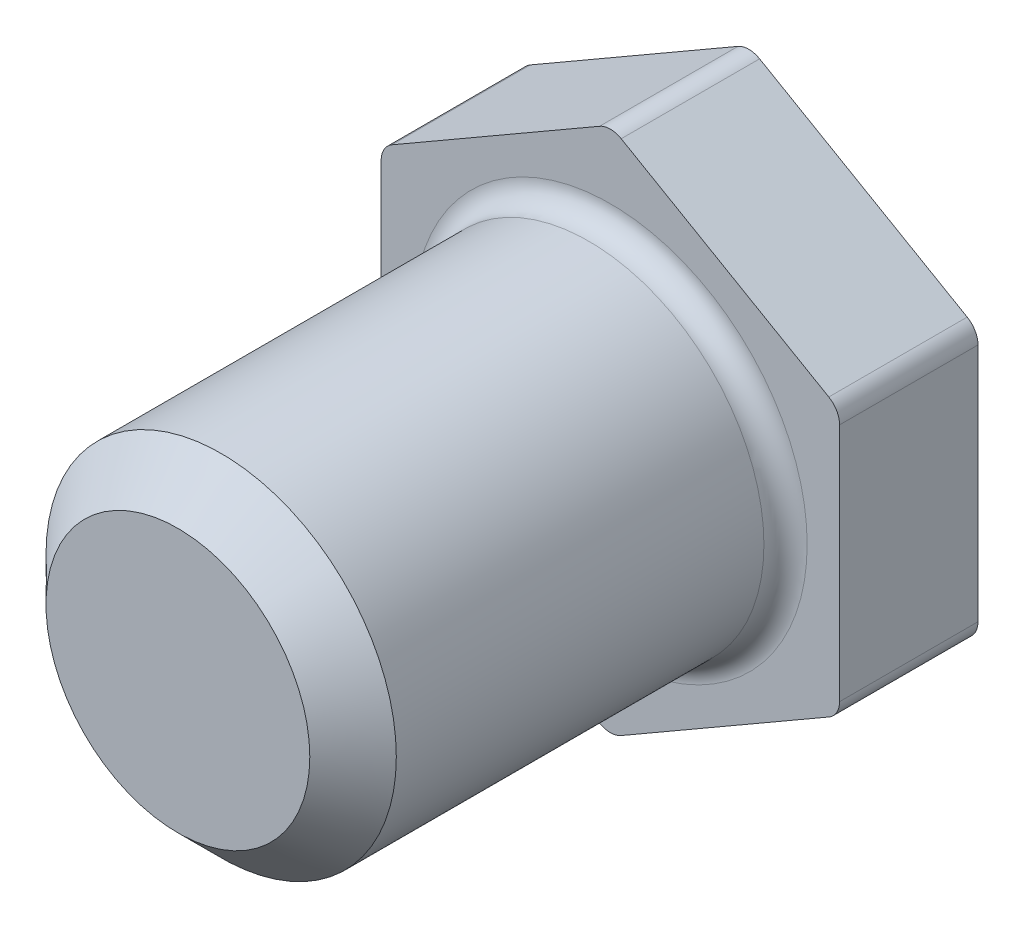
SolidWorks part; units mm, degrees
material "Anycubic PLA V3.0"
ref_plane "Front Plane" through (0, 0, 0) normal (0, 0, 1) x (1, 0, 0)
ref_plane "Top Plane" through (0, 0, 0) normal (0, 1, 0) x (1, 0, 0)
ref_plane "Right Plane" through (0, 0, 0) normal (1, 0, 0) x (0, 0, -1)
sketch "Sketch1" plane through (0, 0, 0) normal (0, 0, 1) x (1, 0, 0)
  line L0 (5.3, 3.06) -> (0, 6.1199)
  line L7 (0, 8.35) -> (-7.2313, 4.175)
  line L8 (-7.2313, 4.175) -> (-7.2313, -4.175)
  line L9 (-7.2313, -4.175) -> (0, -8.35)
  line L10 (0, -8.35) -> (7.2313, -4.175)
  line L11 (7.2313, -4.175) -> (7.2313, 4.175)
  line L12 (7.2313, 4.175) -> (0, 8.35)
  line L13 (0, 6.1199) -> (-5.3, 3.06)
  line L14 (-5.3, 3.06) -> (-5.3, -3.06)
  line L15 (-5.3, -3.06) -> (0, -6.1199)
  line L16 (0, -6.1199) -> (5.3, -3.06)
  line L17 (5.3, -3.06) -> (5.3, 3.06)
  circle A0 centre (0, 0) radius 8.35 construction
  dimension "D1" = 16.7
  dimension "D2" = 10.6
extrude "Boss-Extrude1" add sketch "Sketch1" along normal blind 3.2 contours L0 L13 L14 L15 L16 L17
sketch "Sketch2" plane through (0, 0, 3.2) normal (0, 0, 1) x (1, 0, 0)
  circle A0 centre (0, 0) radius 4.05
  dimension "D1" = 8.1
extrude "Boss-Extrude2" add sketch "Sketch2" along normal blind 10
fillet "Fillet1" radius 0.5 7 edges at (4.05, 0, 3.2) (-5.3, 3.06, 1.6) (-5.3, -3.06, 1.6) (0, -6.1199, 1.6) (5.3, -3.06, 1.6) (5.3, 3.06, 1.6) (0, 6.1199, 1.6)
chamfer "Chamfer1" distance 1 angle 45 1 edges at (4.05, 0, 13.2)
